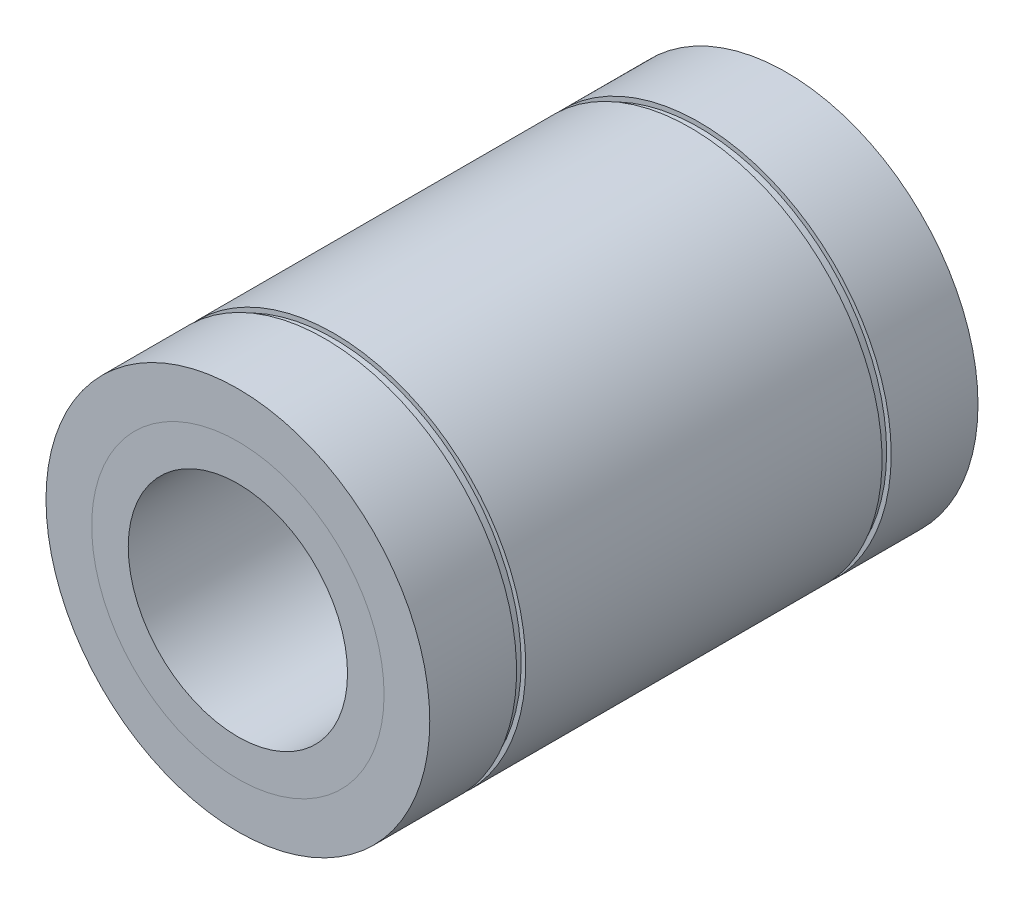
SolidWorks part; units mm, degrees
ref_plane "Front Plane" through (0, 0, 0) normal (0, 0, 1) x (1, 0, 0)
ref_plane "Top Plane" through (0, 0, 0) normal (0, 1, 0) x (1, 0, 0)
ref_plane "Right Plane" through (0, 0, 0) normal (1, 0, 0) x (0, 0, -1)
sketch "Sketch1" plane through (0, 0, 0) normal (0, 0, 1) x (1, 0, 0)
  circle A0 centre (0, 0) radius 10.5
  circle A1 centre (0, 0) radius 8
  dimension "D1" = 21
  dimension "D2" = 16
extrude "Boss-Extrude1" add sketch "Sketch1" along normal mid plane 30
sketch "Sketch2" plane through (0, 0, 0) normal (0, 0, 1) x (1, 0, 0)
  circle A0 centre (0, 0) radius 8
  circle A1 centre (0, 0) radius 6
  dimension "D1" = 12
  dimension "D2" = 16
extrude "Boss-Extrude2" add sketch "Sketch2" along normal mid plane 30 separate body
sketch "Sketch3" plane through (0, 0, 0) normal (0, 1, 0) x (1, 0, 0)
  line L0 (-10.5, -14.2476) -> (-10.5, 49985.7524) construction
  line L2 (-10.5, -15) -> (10.5, -15) construction
  line L3 (-10.75, -9.75) -> (-10.25, -9.75)
  line L4 (-10.75, -9.75) -> (-10.75, -10.25)
  line L5 (-10.75, -10.25) -> (-10.25, -10.25)
  line L6 (-10.25, -9.75) -> (-10.25, -10.25)
  line L7 (-10.75, -9.75) -> (-10.25, -10.25) construction
  line L8 (-10.75, -10.25) -> (-10.25, -9.75) construction
  line L9 (0, 0) -> (50000, 0) construction
  line L10 (-10.75, 10.25) -> (-10.25, 9.75) construction
  line L11 (-10.75, 9.75) -> (-10.25, 10.25) construction
  line L12 (-10.25, 9.75) -> (-10.25, 10.25)
  line L13 (-10.75, 10.25) -> (-10.25, 10.25)
  line L14 (-10.75, 9.75) -> (-10.75, 10.25)
  line L15 (-10.75, 9.75) -> (-10.25, 9.75)
  point P2 (-10.5, -10)
  point P16 (-10.5, 10)
  dimension "D1" = 10.5
  dimension "D2" = 0.5
  dimension "D3" = 0.5
  dimension "D4" = 5
revolve "Cut-Revolve1" cut sketch "Sketch3" angle 360 about axis through (0, 0, 15) along (0, 0, -1)
